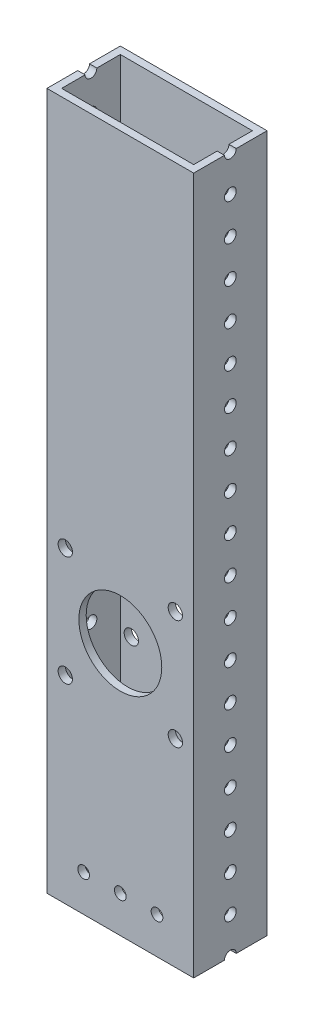
SolidWorks part; units mm, degrees
ref_plane "Front Plane" through (0, 0, 0) normal (0, 0, 1) x (1, 0, 0)
ref_plane "Top Plane" through (0, 0, 0) normal (0, 1, 0) x (1, 0, 0)
ref_plane "Right Plane" through (0, 0, 0) normal (1, 0, 0) x (0, 0, -1)
sketch "Sketch2" plane through (0, 0, 0) normal (0, 1, 0) x (1, 0, 0)
  line L0 (-22.86, 10.16) -> (22.86, 10.16)
  line L1 (-25.4, -12.7) -> (25.4, -12.7)
  line L2 (-25.4, -12.7) -> (-25.4, 12.7)
  line L3 (-25.4, 12.7) -> (25.4, 12.7)
  line L4 (25.4, -12.7) -> (25.4, 12.7)
  line L5 (-25.4, -12.7) -> (25.4, 12.7) construction
  line L6 (-25.4, 12.7) -> (25.4, -12.7) construction
  line L7 (22.86, -10.16) -> (22.86, 10.16)
  line L8 (-22.86, -10.16) -> (22.86, -10.16)
  line L9 (-22.86, -10.16) -> (-22.86, 10.16)
  point P0 (0, 0)
  dimension "D1" = 50.8
  dimension "D2" = 25.4
  dimension "D3" = 2.54
extrude "Boss-Extrude1" add sketch "Sketch2" along normal blind 635
sketch "Sketch3" plane through (25.4, 0, 0) normal (1, 0, 0) x (0, 0, -1)
  line L0 (-12.7, 0) -> (12.7, 0) construction
  circle A0 centre (0, 0) radius 2.032
  circle A1 centre (0, 12.7) radius 2.032
  circle A2 centre (0, 25.4) radius 2.032
  circle A3 centre (0, 38.1) radius 2.032
  circle A4 centre (0, 50.8) radius 2.032
  circle A5 centre (0, 63.5) radius 2.032
  circle A6 centre (0, 76.2) radius 2.032
  circle A7 centre (0, 88.9) radius 2.032
  circle A8 centre (0, 101.6) radius 2.032
  circle A9 centre (0, 114.3) radius 2.032
  circle A10 centre (0, 127) radius 2.032
  circle A11 centre (0, 139.7) radius 2.032
  circle A12 centre (0, 152.4) radius 2.032
  circle A13 centre (0, 165.1) radius 2.032
  circle A14 centre (0, 177.8) radius 2.032
  circle A15 centre (0, 190.5) radius 2.032
  circle A16 centre (0, 203.2) radius 2.032
  circle A17 centre (0, 215.9) radius 2.032
  circle A18 centre (0, 228.6) radius 2.032
  circle A19 centre (0, 241.3) radius 2.032
  circle A20 centre (0, 254) radius 2.032
  circle A21 centre (0, 266.7) radius 2.032
  circle A22 centre (0, 279.4) radius 2.032
  circle A23 centre (0, 292.1) radius 2.032
  circle A24 centre (0, 304.8) radius 2.032
  circle A25 centre (0, 317.5) radius 2.032
  circle A26 centre (0, 330.2) radius 2.032
  circle A27 centre (0, 342.9) radius 2.032
  circle A28 centre (0, 355.6) radius 2.032
  circle A29 centre (0, 368.3) radius 2.032
  circle A30 centre (0, 381) radius 2.032
  circle A31 centre (0, 393.7) radius 2.032
  circle A32 centre (0, 406.4) radius 2.032
  circle A33 centre (0, 419.1) radius 2.032
  circle A34 centre (0, 431.8) radius 2.032
  circle A35 centre (0, 444.5) radius 2.032
  circle A36 centre (0, 457.2) radius 2.032
  circle A37 centre (0, 469.9) radius 2.032
  circle A38 centre (0, 482.6) radius 2.032
  circle A39 centre (0, 495.3) radius 2.032
  circle A40 centre (0, 508) radius 2.032
  circle A41 centre (0, 520.7) radius 2.032
  circle A42 centre (0, 533.4) radius 2.032
  circle A43 centre (0, 546.1) radius 2.032
  circle A44 centre (0, 558.8) radius 2.032
  circle A45 centre (0, 571.5) radius 2.032
  circle A46 centre (0, 584.2) radius 2.032
  circle A47 centre (0, 596.9) radius 2.032
  circle A48 centre (0, 609.6) radius 2.032
  circle A49 centre (0, 622.3) radius 2.032
  dimension "D1" = 4.064
  dimension "D2" = 50
extrude "Cut-Extrude1" cut sketch "Sketch3" against normal through all
sketch "Sketch4" plane through (0, 0, 12.7) normal (0, 0, 1) x (1, 0, 0)
  line L0 (-25.4, 635) -> (-25.4, 0) construction
  line L1 (-25.4, 0) -> (25.4, 0) construction
  circle A0 centre (-12.7, 12.7) radius 2.032
  circle A1 centre (0, 12.7) radius 2.032
  circle A2 centre (12.7, 12.7) radius 2.032
  dimension "D1" = 4.064
  dimension "D2" = 12.7
  dimension "D3" = 12.7
  dimension "D4" = 3
extrude "Cut-Extrude2" cut sketch "Sketch4" against normal through all
sketch "Sketch5" plane through (0, 0, 12.7) normal (0, 0, 1) x (1, 0, 0)
  line L1 (-25.4, 635) -> (-25.4, 0) construction
  line L2 (-25.4, 0) -> (25.4, 0) construction
  line L3 (0, 113.03) -> (0, 62.23) construction
  line L4 (-25.4, 62.23) -> (25.4, 62.23) construction
  line L5 (-25.4, 62.23) -> (-25.4, 113.03) construction
  line L6 (-25.4, 113.03) -> (25.4, 113.03) construction
  line L7 (25.4, 62.23) -> (25.4, 113.03) construction
  line L8 (-25.4, 62.23) -> (25.4, 113.03) construction
  line L9 (-25.4, 113.03) -> (25.4, 62.23) construction
  line L10 (-25.4, 87.63) -> (25.4, 87.63) construction
  circle A0 centre (0, 87.63) radius 14.351
  circle A2 centre (-19.05, 106.68) radius 2.4793
  circle A3 centre (19.05, 106.68) radius 2.4793
  circle A4 centre (19.05, 68.58) radius 2.4793
  circle A5 centre (-19.05, 68.58) radius 2.4793
  dimension "D1" = 28.702
  dimension "D6" = 6.35
  dimension "D2" = 87.63
  dimension "D3" = 50.8
  dimension "D4" = 50.8
  dimension "D7" = 6.35
extrude "Cut-Extrude3" cut sketch "Sketch5" against normal through all
sketch "Sketch6" plane through (0, 635, 0) normal (0, 1, 0) x (1, 0, 0)
  line L4 (25.4, -12.7) -> (25.4, 12.7)
  line L5 (25.4, 12.7) -> (-25.4, 12.7)
  line L6 (-25.4, 12.7) -> (-25.4, -12.7)
  line L7 (-25.4, -12.7) -> (25.4, -12.7)
  line L8 (25.4, -12.7) -> (25.4, 12.7)
  line L9 (25.4, 12.7) -> (-25.4, 12.7)
  line L10 (-25.4, 12.7) -> (-25.4, -12.7)
  line L11 (-25.4, -12.7) -> (25.4, -12.7)
  dimension "D1" = 0
extrude "Cut-Extrude4" cut sketch "Sketch6" against normal blind 355.6
sketch "Sketch10" plane through (0, 0, 12.7) normal (0, 0, 1) x (1, 0, 0)
  line L0 (-25.4, 279.4) -> (25.4, 279.4) construction
  line L5 (-25.4, 279.4) -> (-25.4, 0) construction
  circle A0 centre (-17.78, 157.48) radius 2.1828
  dimension "D1" = 4.3656
  dimension "D2" = 121.92
  dimension "D3" = 7.62
sketch "Sketch11" plane through (0, 0, -12.7) normal (0, 0, -1) x (-1, 0, 0)
  line L0 (-25.4, 279.4) -> (25.4, 279.4) construction
  line L1 (25.4, 279.4) -> (25.4, 0) construction
  circle A0 centre (12.7, 189.23) radius 9.525
  dimension "D1" = 19.05
  dimension "D2" = 90.17
  dimension "D3" = 12.7
extrude "Cut-Extrude7" [suppressed] cut sketch "Sketch10" against normal up to next
extrude "Cut-Extrude8" [suppressed] cut sketch "Sketch11" against normal up to next
sketch "Sketch12" plane through (0, 279.4, 0) normal (0, 1, 0) x (1, 0, 0)
  line L1 (25.4, -12.7) -> (-25.4, -12.7)
  line L2 (25.4, -12.7) -> (25.4, 12.7)
  line L3 (25.4, 12.7) -> (-25.4, 12.7)
  line L4 (-25.4, -12.7) -> (-25.4, 12.7)
extrude "Cut-Extrude9" cut sketch "Sketch12" against normal blind 38.1
